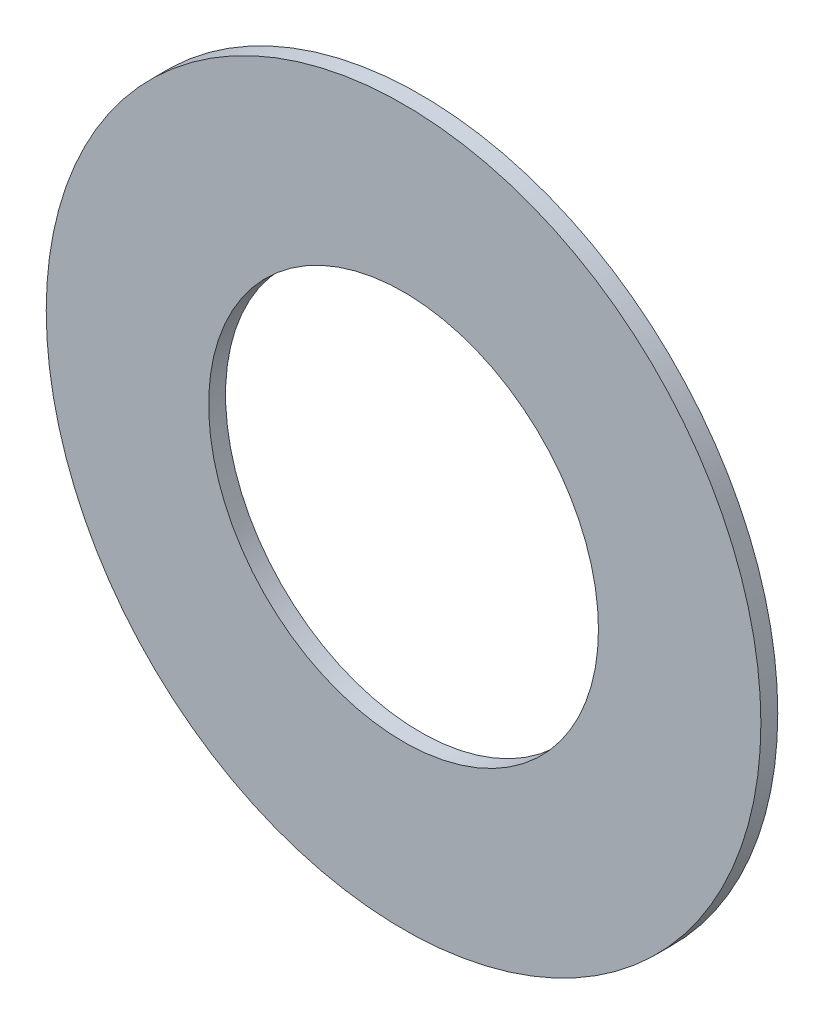
SolidWorks part; units mm, degrees
ref_plane "Front Plane" through (0, 0, 0) normal (0, 0, 1) x (1, 0, 0)
ref_plane "Top Plane" through (0, 0, 0) normal (0, 1, 0) x (1, 0, 0)
ref_plane "Right Plane" through (0, 0, 0) normal (1, 0, 0) x (0, 0, -1)
sketch "Sketch1" plane through (0, 0, 0) normal (0, 0, 1) x (1, 0, 0)
  circle A0 centre (0, 0) radius 1.5
  circle A1 centre (0, 0) radius 2.75
extrude "Boss-Extrude3" add sketch "Sketch1" along normal blind 0.2
sketch "Sketch2" plane through (0, 0, 0.2) normal (0, 0, 1) x (1, 0, 0)
  circle A0 centre (0, 0) radius 4.8359
extrude "Cut-Extrude1" cut sketch "Sketch2" against normal blind 0.07
